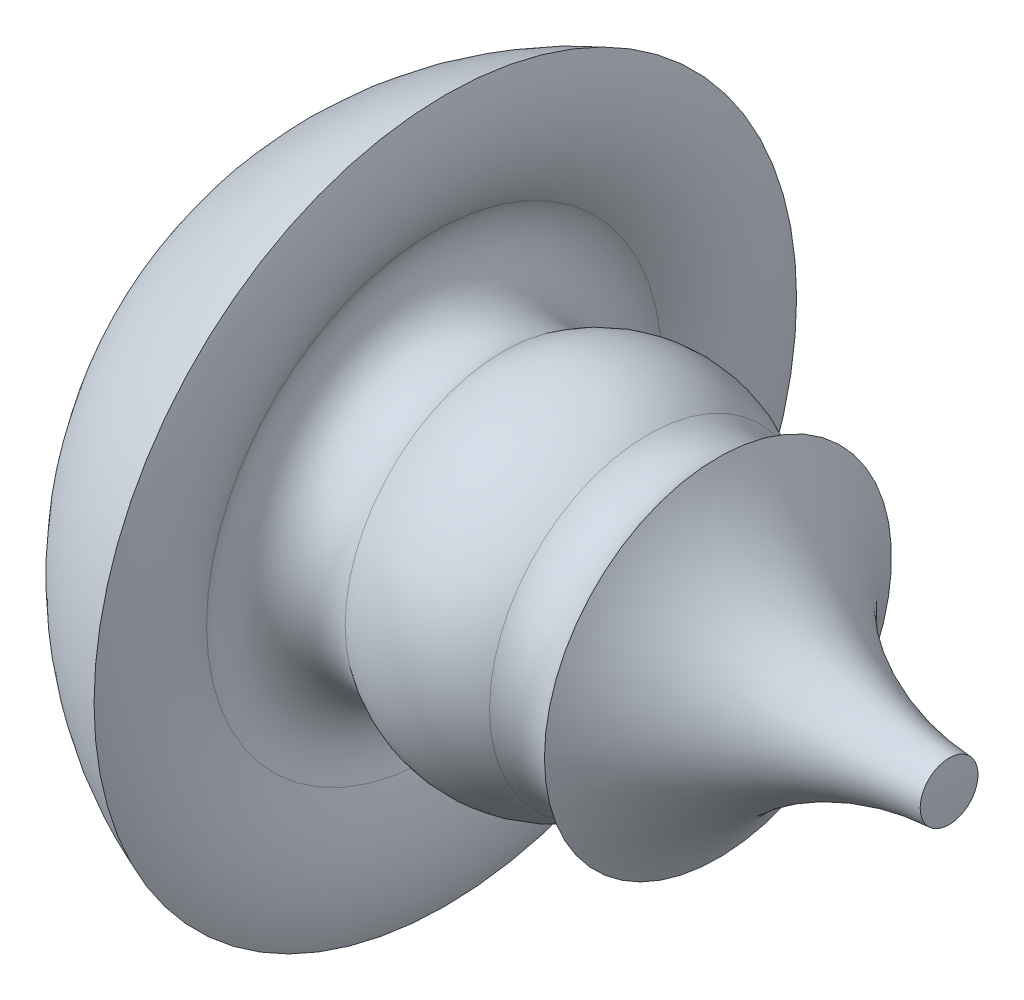
SolidWorks part; units mm, degrees
ref_plane "前基準面" through (0, 0, 0) normal (0, 0, 1) x (1, 0, 0)
ref_plane "上基準面" through (0, 0, 0) normal (0, 1, 0) x (1, 0, 0)
ref_plane "右基準面" through (0, 0, 0) normal (1, 0, 0) x (0, 0, -1)
sketch "草圖1" plane through (0, 0, 0) normal (0, 0, 1) x (1, 0, 0)
  line L0 (0, 150) -> (0, -150) construction
  line L1 (0, 150) -> (0, -150)
  arc A0 (0, -150) -> (0, 150) centre (0, 0) ccw
  dimension "D1" = 150
revolve "旋轉1" add sketch "草圖1" angle 360 about L0
sketch "草圖2" plane through (0, 0, 0) normal (0, 0, 1) x (1, 0, 0)
  line L0 (0, 0) -> (50.6225, 0) construction
  line L2 (0, 120) -> (83.0582, 120) construction
  line L3 (0, 326.361) -> (0, 0) construction
  arc A0 (56.641, 148.906) -> (56.641, 91.094) centre (100, 120) ccw
  arc A1 (-28.906, 176.641) -> (28.906, 176.641) centre (0, 220) ccw
  arc A2 (28.906, 176.641) -> (56.641, 148.906) centre (40, 160) cw
  arc A3 (28.906, 63.359) -> (56.641, 91.094) centre (40, 80) ccw
  arc A4 (-28.906, 176.641) -> (-56.641, 148.906) centre (-40, 160) ccw
  arc A5 (-28.906, 63.359) -> (-56.641, 91.094) centre (-40, 80) cw
  arc A6 (-56.641, 148.906) -> (-56.641, 91.094) centre (-100, 120) cw
  arc A7 (-28.906, 63.359) -> (28.906, 63.359) centre (0, 20) cw
  dimension "D1" = 20
  dimension "D3" = 40
  dimension "D6" = 100
  dimension "D2" = 120
  dimension "D4" = 40
  dimension "D5" = 100
revolve "除料-旋轉1" cut sketch "草圖2" angle 360 about L0
sketch "草圖3" plane through (0, 0, 0) normal (0, 0, 1) x (1, 0, 0)
  line L0 (0, 0) -> (210.532, 0) construction
  circle A0 centre (154.9712, 123.1054) radius 111.6664
revolve "除料-旋轉4" cut sketch "草圖3" angle 360 about L0
